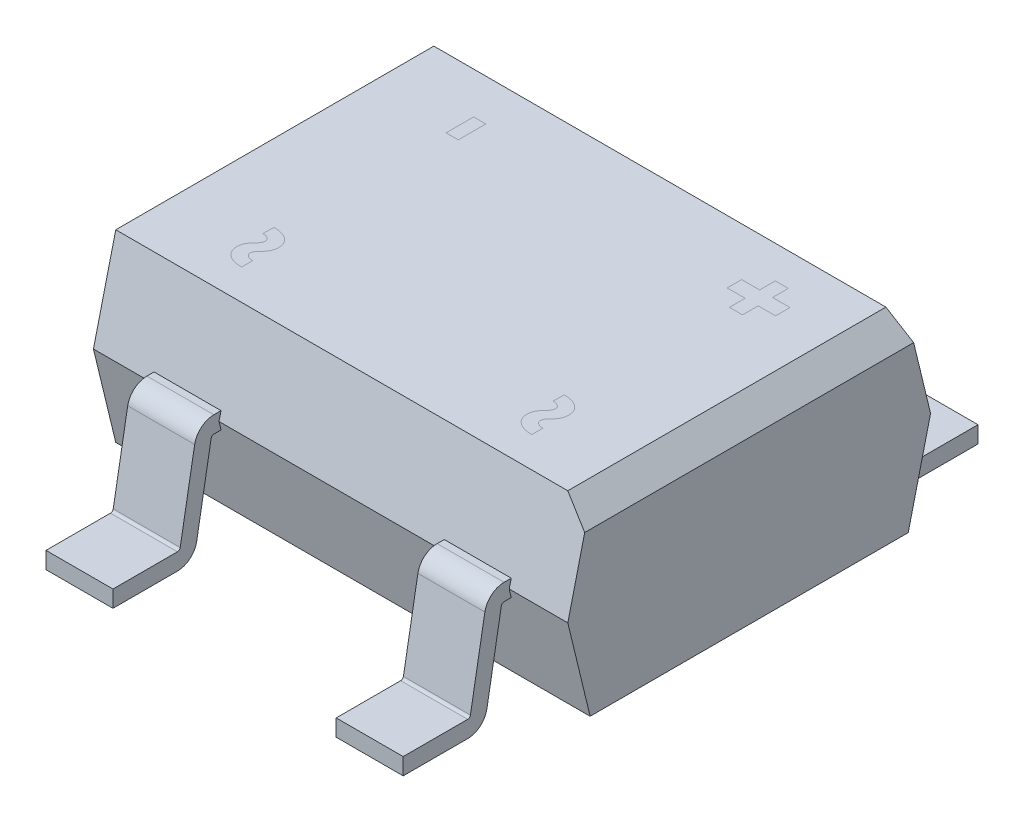
SolidWorks part; units mm, degrees
ref_plane "Front Plane" through (0, 0, 0) normal (0, 0, 1) x (1, 0, 0)
ref_plane "Top Plane" through (0, 0, 0) normal (0, 1, 0) x (1, 0, 0)
ref_plane "Right Plane" through (0, 0, 0) normal (1, 0, 0) x (0, 0, -1)
sketch "Sketch1" plane through (0, 0, 0) normal (1, 0, 0) x (0, 0, -1)
  line L0 (2.85, 0.3) -> (-2.85, 0.3)
  line L1 (-2.85, 0.3) -> (-3.25, 1.95)
  line L2 (-3.25, 1.95) -> (-2.85, 3.6)
  line L3 (-2.85, 3.6) -> (2.85, 3.6)
  line L4 (0, 3.6) -> (0, 0.3) construction
  line L5 (2.85, 0.3) -> (3.25, 1.95)
  line L6 (3.25, 1.95) -> (2.85, 3.6)
  point P2 (0, 0)
  point P6 (-4.1078, 1.9995)
  point P8 (0, 0)
  point P9 (0, 1.95)
  point P10 (-2.7374, 3.6)
  dimension "D1" = 0.3
  dimension "D2" = 3.3
  dimension "D3" = 6.5
  dimension "D4" = 0.4
extrude "Boss-Extrude1" add sketch "Sketch1" along normal mid plane 8.5
chamfer "Chamfer1" distance 0.4 angle 45 1 edges at (4.25, 3.6, 0)
ref_plane "Plane4" through (2.6, 0, 0) normal (1, 0, 0) x (0, 0, -1)
sketch "Sketch2" plane through (2.6, 0, 0) normal (1, 0, 0) x (0, 0, -1)
  line L0 (5.15, 0) -> (3.9947, 0)
  line L1 (3.65, 0.2892) -> (3.3909, 1.7587)
  line L2 (3.3417, 1.8) -> (2.8417, 1.8)
  line L3 (2.8417, 1.8) -> (2.8417, 2.1)
  line L4 (2.8417, 2.1) -> (3.3417, 2.1)
  line L5 (3.6863, 1.8108) -> (3.9454, 0.3413)
  line L6 (3.9947, 0.3) -> (5.15, 0.3)
  line L7 (5.15, 0.3) -> (5.15, 0)
  arc A0 (3.3909, 1.7587) -> (3.3417, 1.8) centre (3.3417, 1.75) ccw
  arc A1 (3.3417, 2.1) -> (3.6863, 1.8108) centre (3.3417, 1.75) cw
  arc A2 (3.9454, 0.3413) -> (3.9947, 0.3) centre (3.9947, 0.35) ccw
  arc A3 (3.9947, 0) -> (3.65, 0.2892) centre (3.9947, 0.35) cw
  point P17 (3.7814, 2.0105)
  point P18 (0, 0)
  point P19 (4.2804, 1.5997)
  point P20 (0, 0)
  point P21 (4.2957, 1.5698)
  point P23 (3.3272, 1.75)
  dimension "D4" = 0.05
  dimension "D1" = 0.3
  dimension "D2" = 1.5
  dimension "D3" = 5.15
  dimension "D5" = 0.15
  dimension "D6" = 0.5
  dimension "D7" = 100
extrude "Boss-Extrude2" add sketch "Sketch2" along normal mid plane 1.2 separate body
pattern_linear "LPattern1" count 2 spacing 5.2 along (-1, 0, 0) of "Boss-Extrude2"
mirror "Mirror2" about plane through (0, 0, 0) normal (0, 0, 1) of bodies 102 103
sketch "Sketch3" plane through (0, 3.6, 0) normal (0, 1, 0) x (1, 0, 0)
  line L0 (2, 2.85) -> (2, 0.85) construction
  line L1 (-3.2, 5.15) -> (-3.2, 3.9947) construction
  line L2 (2, -0.85) -> (2, -2.85) construction
  line L3 (-3.2, -0.85) -> (-3.2, -2.85) construction
  line L4 (-3.2, 2.85) -> (-3.2, 0.85) construction
  line L5 (2, 5.15) -> (2, 3.9947) construction
  line L6 (3.85, 2.85) -> (-4.25, 2.85) construction
  line L7 (3.85, -2.85) -> (-4.25, -2.85) construction
  text T0 "+" font "Roboto Black" height 1.2
  text T1 "~" font "Roboto Black" height 1.2
  text T2 "-" font "Roboto Black" height 1.2
  text T3 "~" font "Roboto Black" height 1.2
  point P2 (-3.3413, -0.6346)
  point P5 (0.8129, -1.3181)
  point P6 (-0.4119, -1.3843)
  point P9 (0, 0)
  point P15 (-3.3413, 2.5263)
  point P20 (0, 0)
  point P21 (0, 0)
  point P24 (0, 0)
  point P25 (0, 0)
  point P28 (0, 0)
  dimension "D1" = 2
  dimension "D2" = 2
  dimension "D3" = 2
  dimension "D4" = 2
split line "Split Line1"
equation "\"D5@Sketch2\"=\"D1@Sketch2\"/2"
equation "\"D2@Sketch3\"=\"D1@Sketch3\""
equation "\"D3@Sketch3\"=\"D2@Sketch3\""
equation "\"D4@Sketch3\"=\"D1@Sketch3\""
